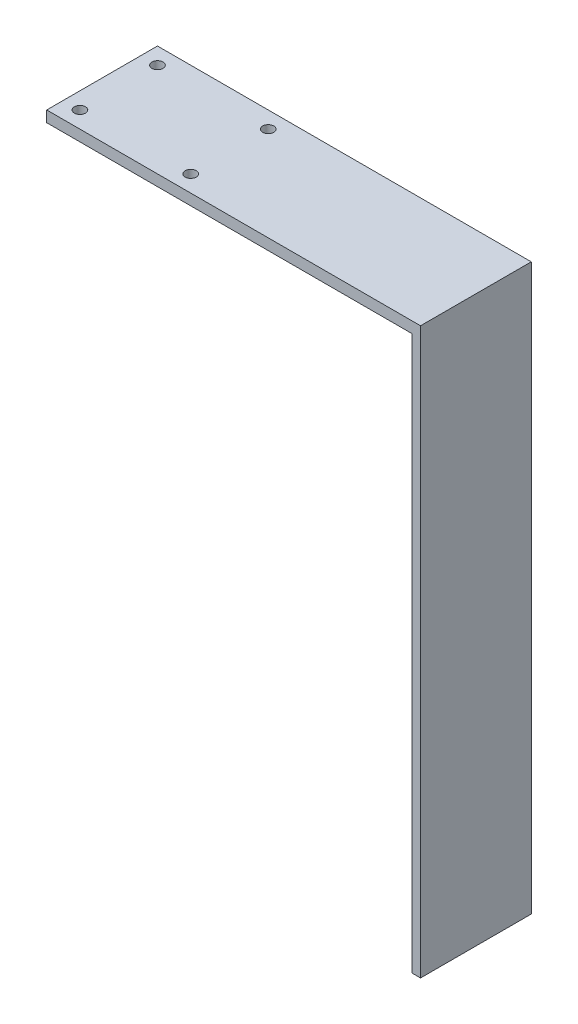
SolidWorks part; units mm, degrees
ref_plane "Front Plane" through (0, 0, 0) normal (0, 0, 1) x (1, 0, 0)
ref_plane "Top Plane" through (0, 0, 0) normal (0, 1, 0) x (1, 0, 0)
ref_plane "Right Plane" through (0, 0, 0) normal (1, 0, 0) x (0, 0, -1)
sketch "Sketch1" plane through (0, 0, 0) normal (0, 1, 0) x (1, 0, 0)
  line L1 (-67.5, 20) -> (67.5, 20)
  line L2 (-67.5, 20) -> (-67.5, -20)
  line L3 (-67.5, -20) -> (67.5, -20)
  line L4 (67.5, 20) -> (67.5, -20)
  line L5 (-67.5, 20) -> (67.5, -20) construction
  line L6 (-67.5, -20) -> (67.5, 20) construction
  line L7 (-61.5, 14) -> (-21.5, 14) construction
  line L8 (-61.5, 14) -> (-61.5, -14) construction
  line L9 (-61.5, -14) -> (-21.5, -14) construction
  line L10 (-21.5, 14) -> (-21.5, -14) construction
  circle A0 centre (-21.5, 14) radius 2
  circle A1 centre (-21.5, -14) radius 2
  circle A2 centre (-61.5, -14) radius 2
  circle A3 centre (-61.5, 14) radius 2
  point P0 (0, 0)
  point P6 (0, 0)
  dimension "D5" = 4
  dimension "D6" = 4
  dimension "D7" = 4
  dimension "D8" = 4
  dimension "D1" = 40
  dimension "D2" = 135
  dimension "D3" = 40
  dimension "D4" = 28
  dimension "D9" = 6
  dimension "D10" = 6
extrude "Boss-Extrude1" add sketch "Sketch1" along normal blind 4
sketch "Sketch3" plane through (0, 0, 0) normal (0, -1, 0) x (1, 0, 0)
  line L0 (67.5, -20) -> (-67.5, -20) construction
  line L1 (67.5, 20) -> (64.5, 20)
  line L2 (67.5, 20) -> (67.5, -20)
  line L3 (67.5, -20) -> (64.5, -20)
  line L4 (64.5, 20) -> (64.5, -20)
  dimension "D1" = 3
extrude "Boss-Extrude3" add sketch "Sketch3" along normal blind 200
